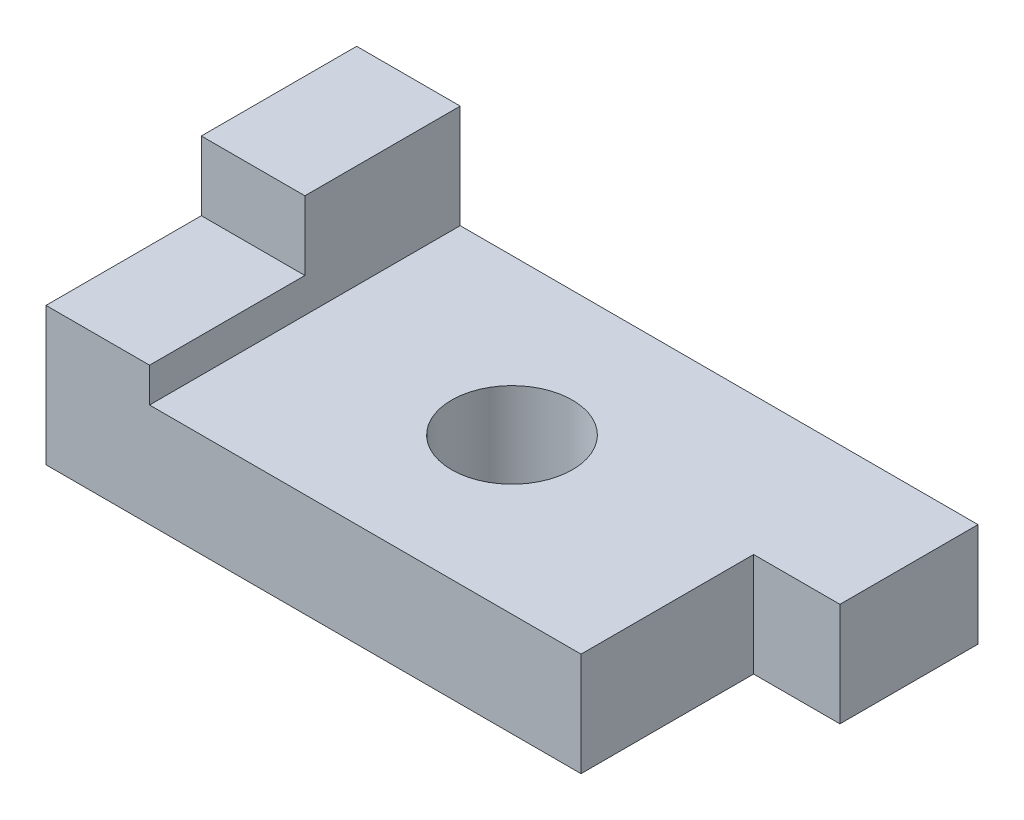
SolidWorks part; units mm, degrees
ref_plane "前基準面" through (0, 0, 0) normal (0, 0, 1) x (1, 0, 0)
ref_plane "上基準面" through (0, 0, 0) normal (0, 1, 0) x (1, 0, 0)
ref_plane "右基準面" through (0, 0, 0) normal (1, 0, 0) x (0, 0, -1)
sketch "草圖1" plane through (0, 0, 0) normal (0, 1, 0) x (1, 0, 0)
  line L0 (0, 0) -> (62, 0)
  line L1 (62, 0) -> (62, 20)
  line L2 (62, 20) -> (72, 20)
  line L3 (72, 20) -> (72, 36)
  line L4 (72, 36) -> (0, 36)
  line L5 (0, 36) -> (0, 0)
  circle A0 centre (36, 18) radius 7
  dimension "D1" = 14
  dimension "D2" = 18
  dimension "D3" = 10
  dimension "D4" = 20
  dimension "D5" = 36
  dimension "D6" = 36
  dimension "D7" = 72
extrude "填料-伸長1" add sketch "草圖1" along normal blind 12
sketch "草圖2" plane through (0, 12, 0) normal (0, 1, 0) x (1, 0, 0)
  line L0 (0, 0) -> (12, 0)
  line L1 (0, 0) -> (62, 0) construction
  line L2 (12, 0) -> (12, 18)
  line L3 (12, 18) -> (0, 18)
  line L5 (0, 36) -> (0, 0) construction
  line L6 (0, 18) -> (0, 0)
  dimension "D1" = 18
  dimension "D2" = 12
extrude "填料-伸長2" add sketch "草圖2" along normal blind 4
sketch "草圖3" plane through (0, 12, 0) normal (0, 1, 0) x (1, 0, 0)
  line L0 (0, 36) -> (0, 18)
  line L1 (0, 18) -> (12, 18)
  line L2 (12, 18) -> (12, 36)
  line L3 (72, 36) -> (0, 36) construction
  line L4 (12, 36) -> (0, 36)
extrude "填料-伸長3" add sketch "草圖3" along normal blind 12
